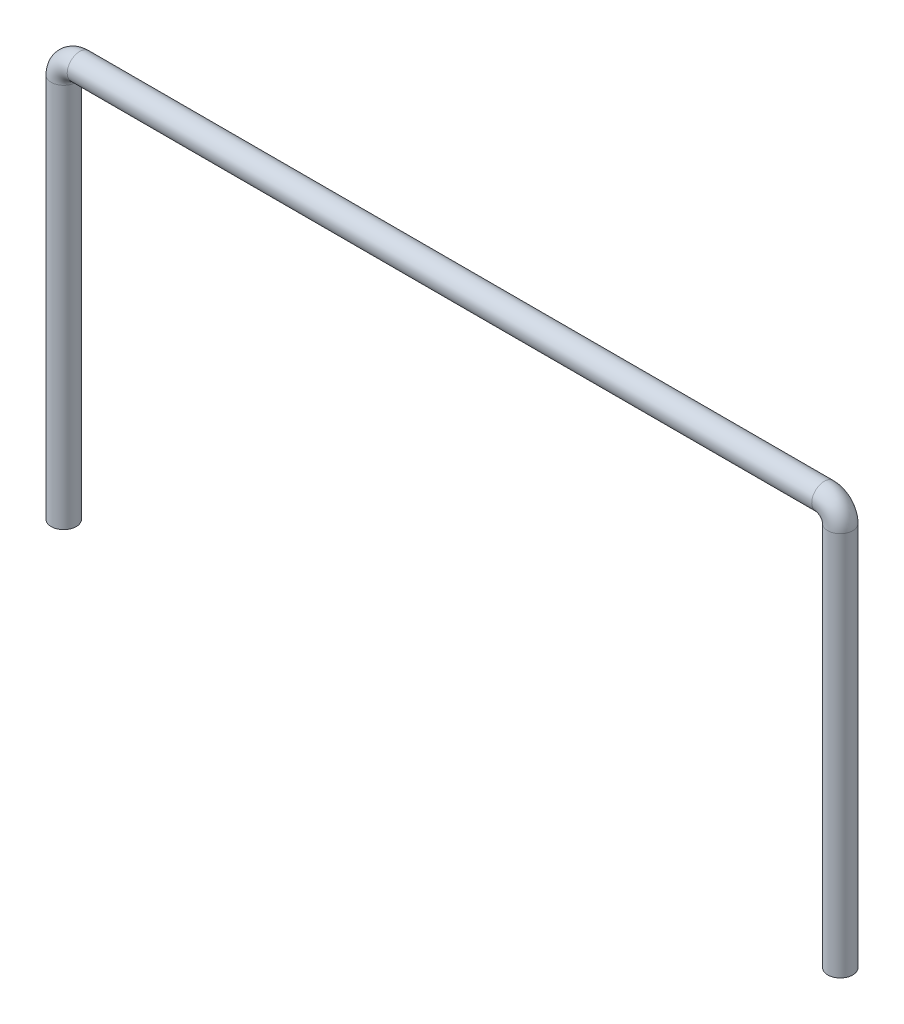
SolidWorks part; units mm, degrees
ref_plane "Front Plane" through (0, 0, 0) normal (0, 0, 1) x (1, 0, 0)
ref_plane "Top Plane" through (0, 0, 0) normal (0, 1, 0) x (1, 0, 0)
ref_plane "Right Plane" through (0, 0, 0) normal (1, 0, 0) x (0, 0, -1)
sketch "Sketch1" plane through (0, 0, 0) normal (0, 0, 1) x (1, 0, 0)
  line L0 (5.8976, 0) -> (-5.8976, 0)
  line L1 (-6.1516, -0.254) -> (-6.1516, -6.35)
  line L2 (6.1516, -0.254) -> (6.1516, -6.35)
  line L3 (0, 0) -> (0, 11.763) construction
  arc A0 (-6.1516, -0.254) -> (-5.8976, 0) centre (-5.8976, -0.254) cw
  arc A1 (6.1516, -0.254) -> (5.8976, 0) centre (5.8976, -0.254) ccw
  point P2 (8.18, 0.1443)
  point P4 (0, 0)
  point P12 (-6.35, -0.2641)
  point P15 (0, 0)
  point P16 (0, 0)
  point P17 (-6.35, -6.35)
  dimension "D3" = 0.254
  dimension "D1" = 6.35
  dimension "D2" = 12.3031
ref_plane "Plane1" through (0, -6.35, 0) normal (0, 1, 0) x (1, 0, 0)
sketch "Sketch2" plane through (0, -6.35, 0) normal (0, 1, 0) x (1, 0, 0)
  line L0 (-6.1516, 0) -> (-5.8976, 0) construction
  circle A0 centre (-6.1516, 0) radius 0.1984
  point P4 (0, 0)
  point P5 (-5.4147, 0)
  point P6 (0, 0)
  point P7 (0, 0)
  point P9 (0, 0)
  point P10 (0, 0)
  point P11 (-6.0153, 0)
  dimension "D1" = 0.3969
sweep "Sweep3" add profiles "Sketch2" path "Sketch1"
